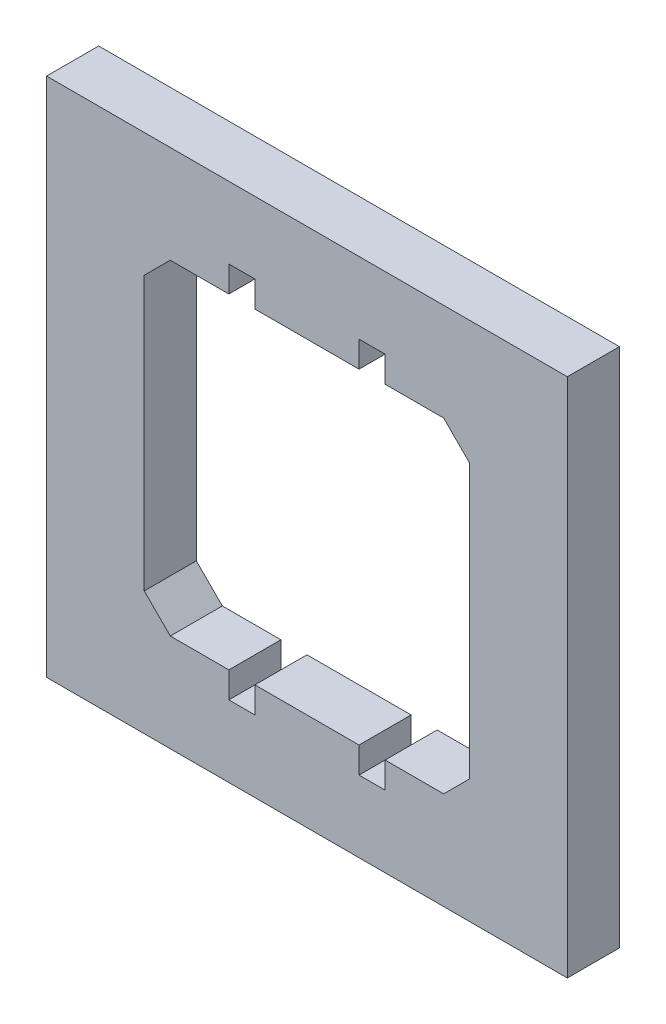
SolidWorks part; units mm, degrees
ref_plane "정면" through (0, 0, 0) normal (0, 0, 1) x (1, 0, 0)
ref_plane "윗면" through (0, 0, 0) normal (0, 1, 0) x (1, 0, 0)
ref_plane "우측면" through (0, 0, 0) normal (1, 0, 0) x (0, 0, -1)
sketch "스케치2" plane through (0, 0, 0) normal (0, 0, 1) x (1, 0, 0)
  line L1 (-10, -10) -> (10, -10)
  line L2 (-10, -10) -> (-10, 10)
  line L3 (-10, 10) -> (10, 10)
  line L4 (10, -10) -> (10, 10)
  line L5 (-10, -10) -> (10, 10) construction
  line L6 (-10, 10) -> (10, -10) construction
  line L7 (-6.25, -6.25) -> (6.25, -6.25)
  line L8 (-6.25, -6.25) -> (-6.25, 6.25)
  line L9 (-6.25, 6.25) -> (6.25, 6.25)
  line L10 (6.25, -6.25) -> (6.25, 6.25)
  line L11 (-6.25, -6.25) -> (6.25, 6.25) construction
  line L12 (-6.25, 6.25) -> (6.25, -6.25) construction
  line L13 (-3, 6.25) -> (-2, 6.25)
  line L14 (-3, 6.25) -> (-3, 7.25)
  line L15 (-3, 7.25) -> (-2, 7.25)
  line L16 (-2, 6.25) -> (-2, 7.25)
  line L17 (2, 6.25) -> (3, 6.25)
  line L18 (2, 6.25) -> (2, 7.25)
  line L19 (2, 7.25) -> (3, 7.25)
  line L20 (3, 6.25) -> (3, 7.25)
  line L21 (-3, -6.25) -> (-2, -6.25)
  line L22 (-3, -6.25) -> (-3, -7.25)
  line L23 (-3, -7.25) -> (-2, -7.25)
  line L24 (-2, -6.25) -> (-2, -7.25)
  line L25 (2, -6.25) -> (3, -6.25)
  line L26 (2, -6.25) -> (2, -7.25)
  line L27 (2, -7.25) -> (3, -7.25)
  line L28 (3, -6.25) -> (3, -7.25)
  point P0 (0, 0)
  point P6 (0, 0)
  point P27 (2, 6.75)
  point P28 (-2, -6.75)
  dimension "D1" = 20
  dimension "D2" = 20
  dimension "D3" = 12.5
  dimension "D4" = 12.5
  dimension "D5" = 4
  dimension "D6" = 4
  dimension "D7" = 1
  dimension "D8" = 1
  dimension "D9" = 1
  dimension "D10" = 1
  dimension "D11" = 1
  dimension "D12" = 1
  dimension "D13" = 1
  dimension "D14" = 1
  dimension "D15" = 2
  dimension "D16" = 2
extrude "보스-돌출1" add sketch "스케치2" along normal blind 2 contours L1 L4 L3 L2 L7 L28 L27 L26 L24 L23 L22 L8 L9 L14 L15 L16 L18 L19 L20 L10
chamfer "모따기1" distance 1 angle 45 4 edges at (-6.25, -6.25, 1) (6.25, -6.25, 1) (6.25, 6.25, 1) (-6.25, 6.25, 1)
